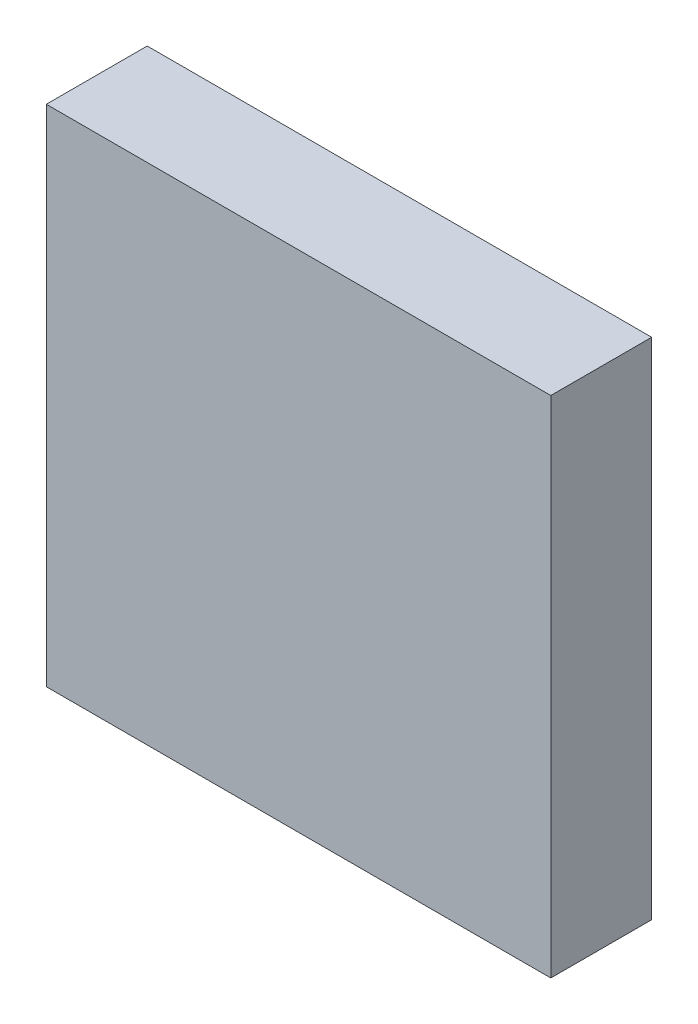
SolidWorks part; units mm, degrees
ref_plane "Front Plane" through (0, 0, 0) normal (0, 0, 1) x (1, 0, 0)
ref_plane "Top Plane" through (0, 0, 0) normal (0, 1, 0) x (1, 0, 0)
ref_plane "Right Plane" through (0, 0, 0) normal (1, 0, 0) x (0, 0, -1)
sketch "Sketch1" plane through (0, 0, 0) normal (0, 0, 1) x (1, 0, 0)
  line L1 (0, 0) -> (25, 0)
  line L2 (0, 0) -> (0, -25)
  line L3 (0, -25) -> (25, -25)
  line L4 (25, 0) -> (25, -25)
  dimension "D1" = 25
extrude "Boss-Extrude1" add sketch "Sketch1" along normal blind 5
